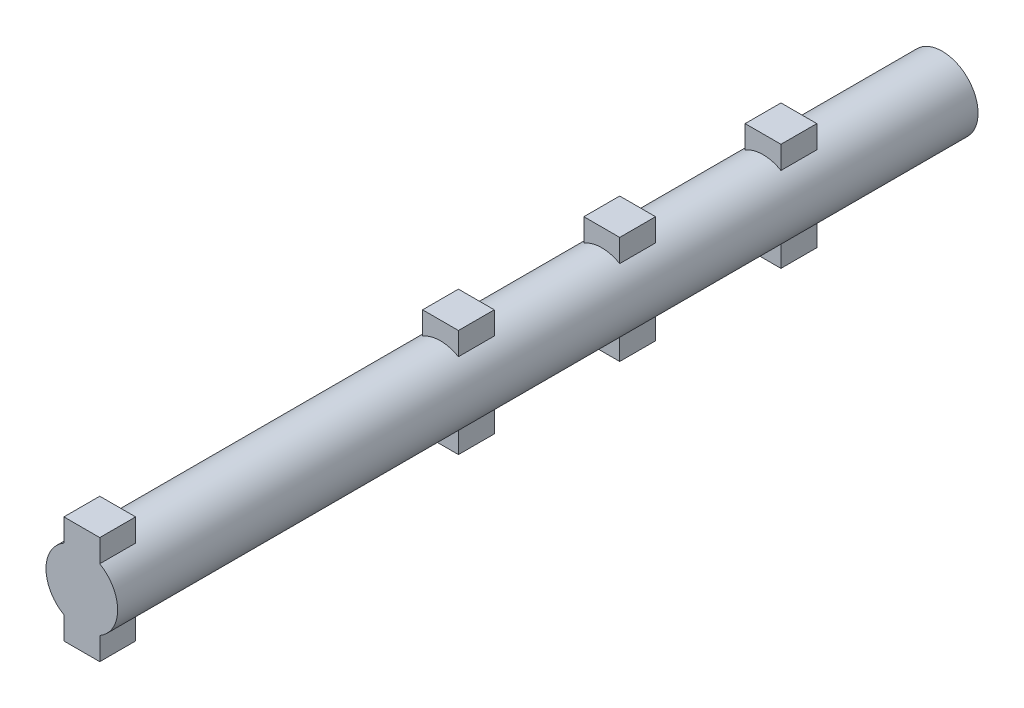
SolidWorks part; units mm, degrees
ref_plane "Front Plane" through (0, 0, 0) normal (0, 0, 1) x (1, 0, 0)
ref_plane "Top Plane" through (0, 0, 0) normal (0, 1, 0) x (1, 0, 0)
ref_plane "Right Plane" through (0, 0, 0) normal (1, 0, 0) x (0, 0, -1)
sketch "Sketch1" plane through (0, 0, 0) normal (0, 0, 1) x (1, 0, 0)
  circle A0 centre (0, 0) radius 5
  dimension "D1" = 10
extrude "Boss-Extrude1" add sketch "Sketch1" along normal blind 25
sketch "Sketch2" plane through (0, 0, 25) normal (0, 0, 1) x (1, 0, 0)
  line L1 (-2.5, -7.5) -> (2.5, -7.5)
  line L2 (-2.5, -7.5) -> (-2.5, 7.5)
  line L3 (-2.5, 7.5) -> (2.5, 7.5)
  line L4 (2.5, -7.5) -> (2.5, 7.5)
  line L5 (-2.5, -7.5) -> (2.5, 7.5) construction
  line L6 (-2.5, 7.5) -> (2.5, -7.5) construction
  point P0 (0, 0)
  dimension "D1" = 15
  dimension "D2" = 5
extrude "Boss-Extrude2" add sketch "Sketch2" against normal blind 5
sketch "Sketch3" plane through (0, 0, 0) normal (0, 0, -1) x (-1, 0, 0)
  line L1 (-2.5, -7.5) -> (2.5, -7.5)
  line L2 (-2.5, -7.5) -> (-2.5, 7.5)
  line L3 (-2.5, 7.5) -> (2.5, 7.5)
  line L4 (2.5, -7.5) -> (2.5, 7.5)
  line L5 (-2.5, -7.5) -> (2.5, 7.5) construction
  line L6 (-2.5, 7.5) -> (2.5, -7.5) construction
  point P0 (0, 0)
  dimension "D1" = 15
  dimension "D2" = 5
extrude "Boss-Extrude3" add sketch "Sketch3" against normal blind 2.5
sketch "Sketch5" plane through (0, 0, 0) normal (0, 0, -1) x (-1, 0, 0)
  line L0 (2.5, 4.3301) -> (2.5, 7.5) construction
  line L1 (-2.5, -7.5) -> (2.5, -7.5)
  line L2 (-2.5, -7.5) -> (-2.5, 7.5)
  line L3 (-2.5, 7.5) -> (2.5, 7.5)
  line L4 (2.5, -7.5) -> (2.5, 7.5)
  line L5 (-2.5, -7.5) -> (2.5, 7.5) construction
  line L6 (-2.5, 7.5) -> (2.5, -7.5) construction
  point P0 (0, 0)
extrude "Boss-Extrude5" add sketch "Sketch5" along normal blind 2.5
sketch "Sketch6" plane through (0, 0, 0) normal (0, 0, -1) x (-1, 0, 0)
  circle A0 centre (0, 0) radius 5
extrude "Boss-Extrude6" add sketch "Sketch6" along normal blind 25
sketch "Sketch7" plane through (0, 0, -25) normal (0, 0, -1) x (-1, 0, 0)
  line L1 (2.5, -7.5) -> (-2.5, -7.5)
  line L2 (2.5, -7.5) -> (2.5, 7.5)
  line L3 (2.5, 7.5) -> (-2.5, 7.5)
  line L4 (-2.5, -7.5) -> (-2.5, 7.5)
  line L5 (2.5, -7.5) -> (-2.5, 7.5) construction
  line L6 (2.5, 7.5) -> (-2.5, -7.5) construction
  point P0 (0, 0)
  dimension "D1" = 15
  dimension "D2" = 5
extrude "Boss-Extrude7" add sketch "Sketch7" against normal blind 5
hole_wizard "Ø5.0mm Dowel Hole1" positions "Sketch11" profile "Sketch12" hole size "Ø5.0" standard "ANSI Metric" end condition through all
sketch "Sketch11" plane through (0, 0, 25) normal (0, 0, 1) x (1, 0, 0)
  point P0 (0, 0)
sketch "Sketch12" plane through (0, 0, 25) normal (1, 0, 0) x (0, -1, 0)
  line L0 (0, 0) -> (0, 50)
  line L1 (0, 50) -> (2.5, 50)
  line L2 (2.5, 50) -> (2.5, 0)
  line L5 (2.5, 0) -> (0, 0)
  line L11 (0, -6.35) -> (0, 107.95) construction
  dimension "Thru Hole Dia." = 5
  dimension "Thru Hole Depth" = 50
sketch "Sketch14" plane through (0, 0, -25) normal (0, 0, -1) x (-1, 0, 0)
  circle A0 centre (0, 0) radius 5
extrude "Boss-Extrude8" add sketch "Sketch14" along normal blind 20
sketch "Sketch15" plane through (0, 0, 25) normal (0, 0, 1) x (1, 0, 0)
  circle A0 centre (0, 0) radius 5
extrude "Boss-Extrude9" add sketch "Sketch15" along normal blind 50.044
sketch "Sketch18" plane through (0, 0, 75.044) normal (0, 0, 1) x (1, 0, 0)
  line L1 (-2.5, 7.5) -> (2.5, 7.5)
  line L2 (-2.5, 7.5) -> (-2.5, -7.5)
  line L3 (-2.5, -7.5) -> (2.5, -7.5)
  line L4 (2.5, 7.5) -> (2.5, -7.5)
  line L5 (-2.5, 7.5) -> (2.5, -7.5) construction
  line L6 (-2.5, -7.5) -> (2.5, 7.5) construction
  point P0 (0, 0)
  dimension "D1" = 15
  dimension "D2" = 5
extrude "Boss-Extrude10" add sketch "Sketch18" against normal blind 5
hole_wizard "Ø5.0mm Dowel Hole2" positions "Sketch16" profile "Sketch17" hole size "Ø5.0" standard "ANSI Metric"
sketch "Sketch16" plane through (0, 0, -45) normal (0, 0, -1) x (-1, 0, 0)
  point P0 (0, 0)
sketch "Sketch17" plane through (0, 0, -45) normal (1, 0, 0) x (0, 1, 0)
  line L0 (0, 0) -> (0, 90)
  line L1 (0, 90) -> (2.5, 90)
  line L2 (2.5, 90) -> (2.5, 0)
  line L5 (2.5, 0) -> (0, 0)
  line L11 (0, -6.35) -> (0, 107.95) construction
  dimension "Thru Hole Dia." = 5
  dimension "Thru Hole Depth" = 90
